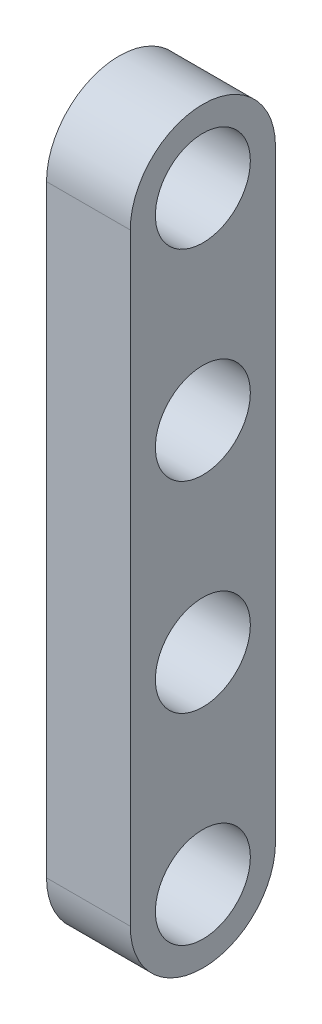
SolidWorks part; units mm, degrees
material "Медь"
ref_plane "Спереди" through (0, 0, 0) normal (0, 0, 1) x (1, 0, 0)
ref_plane "Сверху" through (0, 0, 0) normal (0, 1, 0) x (1, 0, 0)
ref_plane "Справа" through (0, 0, 0) normal (1, 0, 0) x (0, 0, -1)
sketch "Эскиз1" plane through (0, 0, 0) normal (1, 0, 0) x (0, 0, -1)
  line L0 (-4.835, 18) -> (-4.835, -18)
  line L1 (4.835, 18) -> (4.835, -18)
  circle A0 centre (0, 18) radius 2.835
  circle A1 centre (0, 6) radius 2.835
  circle A2 centre (0, -6) radius 2.835
  circle A3 centre (0, -18) radius 2.835
  arc A4 (-4.835, -18) -> (4.835, -18) centre (0, -18) ccw
  arc A5 (4.835, 18) -> (-4.835, 18) centre (0, 18) ccw
extrude "Бобышка-Вытянуть1" add sketch "Эскиз1" along normal blind 5
sketch "Эскиз2" plane through (5, 0, 0) normal (1, 0, 0) x (0, 0, -1)
  line L2 (-4.835, 18) -> (-4.835, -18)
  line L3 (4.835, -18) -> (4.835, 18)
  line L4 (-4.335, 18) -> (-4.335, -18)
  line L5 (4.335, -18) -> (4.335, 18)
  line L6 (-4.335, 18) -> (-4.335, -18)
  line L7 (4.335, -18) -> (4.335, 18)
  arc A2 (4.835, 18) -> (-4.835, 18) centre (0, 18) ccw
  arc A3 (-4.835, -18) -> (4.835, -18) centre (0, -18) ccw
  arc A4 (4.335, 18) -> (-4.335, 18) centre (0, 18) ccw
  arc A5 (-4.335, -18) -> (4.335, -18) centre (0, -18) ccw
  arc A6 (4.335, 18) -> (-4.335, 18) centre (0, 18) ccw
  arc A7 (-4.335, -18) -> (4.335, -18) centre (0, -18) ccw
  dimension "D1" = 0.5
  dimension "D2" = 0.5
extrude "Вырез-Вытянуть1" cut sketch "Эскиз2" against normal blind 5
